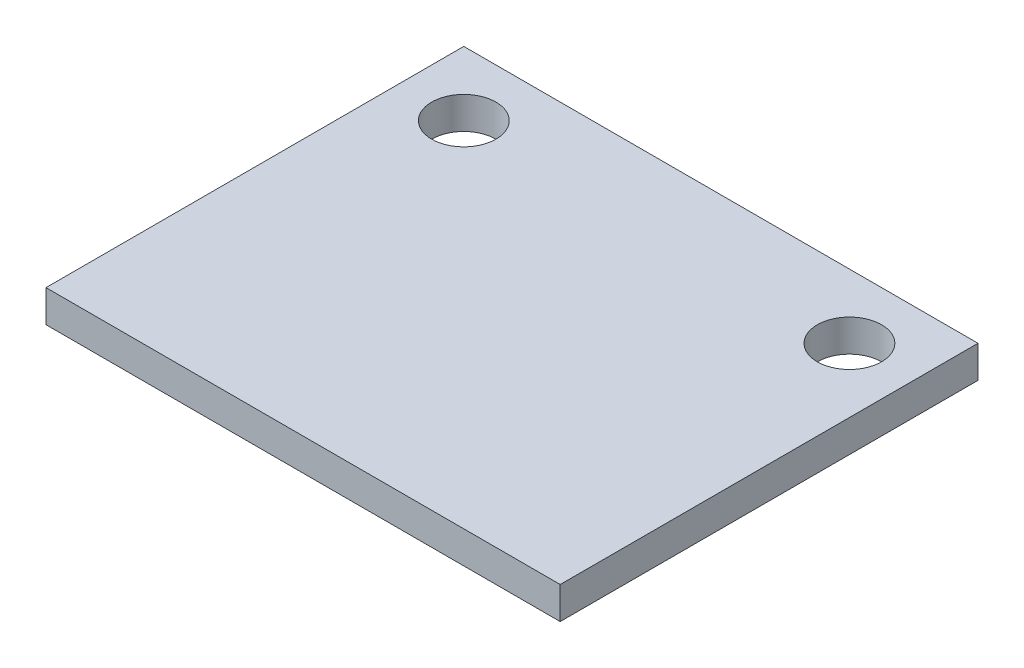
SolidWorks part; units mm, degrees
ref_plane "Front Plane" through (0, 0, 0) normal (0, 0, 1) x (1, 0, 0)
ref_plane "Top Plane" through (0, 0, 0) normal (0, 1, 0) x (1, 0, 0)
ref_plane "Right Plane" through (0, 0, 0) normal (1, 0, 0) x (0, 0, -1)
sketch "Sketch1" plane through (0, 0, 0) normal (0, 1, 0) x (1, 0, 0)
  line L0 (0, 40) -> (0, -40) construction
  line L1 (-40, -40) -> (40, -40)
  line L2 (-40, -40) -> (-40, 40)
  line L3 (-40, 40) -> (40, 40)
  line L4 (40, -40) -> (40, 40)
  line L5 (-40, -40) -> (40, 40) construction
  line L6 (-40, 40) -> (40, -40) construction
  line L7 (0, 0) -> (-30, 0) construction
  line L8 (-30, -40) -> (-30, 30) construction
  line L9 (-25, 30) -> (25, 30) construction
  line L10 (-23, 22) -> (-23, 38)
  line L11 (-25, 20) -> (25, 20)
  line L12 (-25, 20) -> (-25, 40)
  line L13 (-25, 40) -> (25, 40)
  line L14 (25, 20) -> (25, 40)
  line L15 (-25, 20) -> (25, 40) construction
  line L16 (-25, 40) -> (25, 20) construction
  line L18 (23, 22) -> (23, 38)
  line L20 (-23, 38) -> (23, 38) construction
  line L21 (-23, 22) -> (23, 22) construction
  line L22 (30, 30) -> (40, 30) construction
  line L24 (-40, -40) -> (40, -40)
  line L25 (-40, -40) -> (-40, -25)
  line L26 (-40, -25) -> (40, -25)
  line L27 (40, -40) -> (40, -25)
  circle A0 centre (-30, 30) radius 5
  circle A1 centre (30, 30) radius 5
  point P0 (0, 0)
  point P17 (0, 30)
  dimension "D1" = 2
  dimension "D2" = 15
extrude "Boss-Extrude1" add sketch "Sketch1" along normal blind 5
scale "Scale2" scale about centroid uniform scaling yes scale factor 0.1
